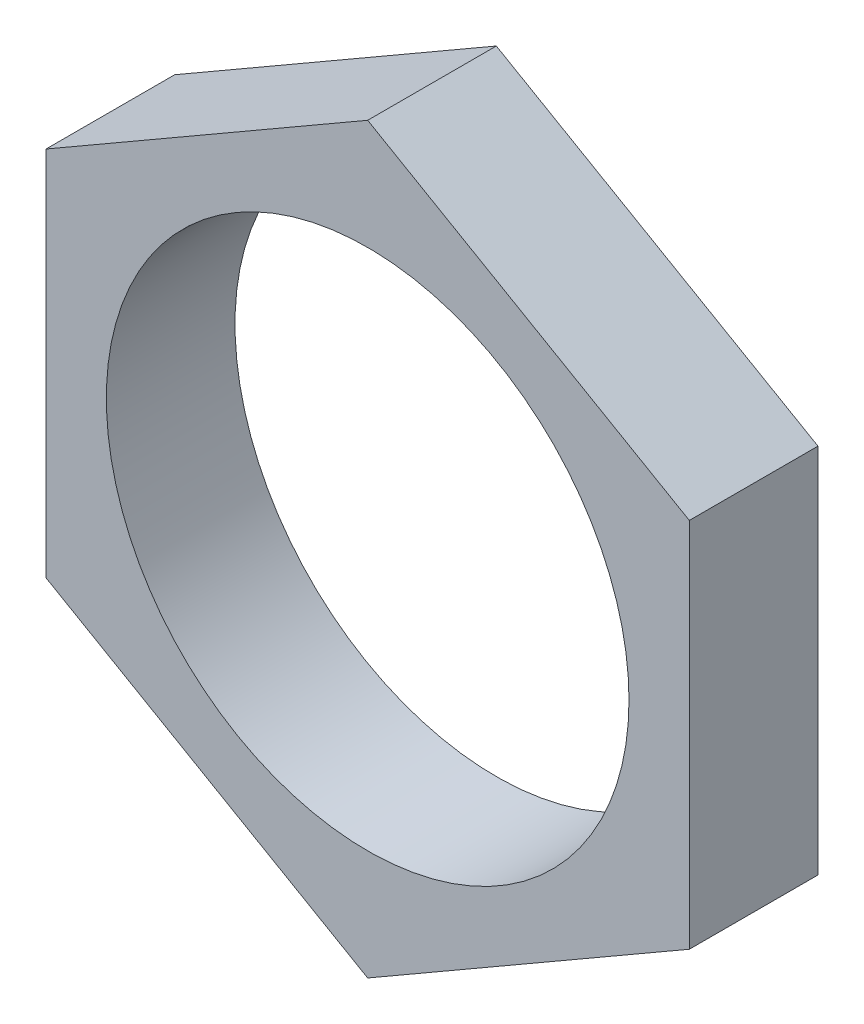
SolidWorks part; units mm, degrees
material "Латунь"
ref_plane "Спереди" through (0, 0, 0) normal (0, 0, 1) x (1, 0, 0)
ref_plane "Сверху" through (0, 0, 0) normal (0, 1, 0) x (1, 0, 0)
ref_plane "Справа" through (0, 0, 0) normal (1, 0, 0) x (0, 0, -1)
sketch "Эскиз1" plane through (0, 0, 0) normal (0, 0, 1) x (1, 0, 0)
  line L0 (-4, 2.3094) -> (-4, -2.3094)
  line L1 (-4, -2.3094) -> (0, -4.6188)
  line L2 (0, -4.6188) -> (4, -2.3094)
  line L3 (4, -2.3094) -> (4, 2.3094)
  line L4 (4, 2.3094) -> (0, 4.6188)
  line L5 (0, 4.6188) -> (-4, 2.3094)
  circle A0 centre (0, 0) radius 4 construction
  circle A1 centre (0, 0) radius 3.25
  dimension "D1" = 6.5
  dimension "D2" = 8
extrude "Вытянуть1" add sketch "Эскиз1" along normal blind 1.6
